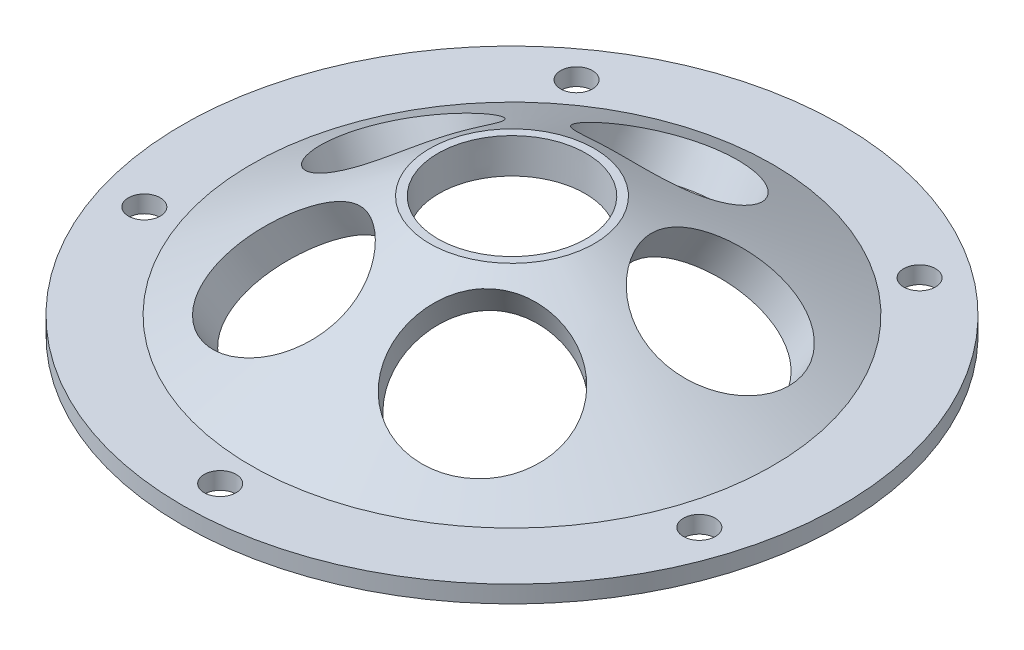
SolidWorks part; units mm, degrees
ref_plane "Front Plane" through (0, 0, 0) normal (0, 0, 1) x (1, 0, 0)
ref_plane "Top Plane" through (0, 0, 0) normal (0, 1, 0) x (1, 0, 0)
ref_plane "Right Plane" through (0, 0, 0) normal (1, 0, 0) x (0, 0, -1)
sketch "Sketch1" plane through (0, 0, 0) normal (0, 0, 1) x (1, 0, 0)
  line L0 (0, 0) -> (0, 62.5338) construction
  line L1 (-13.112, 0.0042) -> (-11.5245, -2.7454) construction
  line L2 (-7.62, 3.175) -> (0, 3.175)
  line L3 (0, 3.175) -> (0, 0)
  line L4 (0, 0) -> (-6.7693, 0)
  line L5 (-20.5296, -7.9446) -> (-6.7693, 0)
  line L6 (-20.5296, -7.9446) -> (-30.48, -7.9446)
  line L7 (-24.13, -6.3571) -> (-7.62, 3.175)
  line L8 (-24.13, -6.3571) -> (-30.48, -6.3571)
  line L9 (-30.48, -6.3571) -> (-30.48, -7.9446)
  dimension "D5" = 30.48
  dimension "D1" = 3.175
  dimension "D2" = 30
  dimension "D3" = 1.5875
  dimension "D4" = 3.175
  dimension "D6" = 7.62
  dimension "D7" = 30
  dimension "D8" = 6.35
revolve "Revolve1" add sketch "Sketch1" angle 360 about L0
hole_wizard "7/16 (0.4375) Diameter Hole1" positions "3DSketch3" profile "Sketch13" hole size "7/16" standard "ANSI Inch"
sketch3d "3DSketch3"
  line L0 (0, 0, 0) -> (-0.4067, -1.1972, -15.1875) construction
  point P0 (-0.4067, -1.1972, -15.1875)
  point P3 (0, 0, 0)
  dimension "D1" = 15.24
sketch "Sketch13" plane through (-0.4067, -1.1972, -15.1875) normal (0.6522, 0.3865, 0.6522) x (-0.758, 0.3172, 0.57)
  line L0 (0, 0) -> (0, 32.3745)
  line L1 (0, 32.3745) -> (5.5562, 32.3745)
  line L2 (5.5562, 32.3745) -> (5.5562, 0)
  line L5 (5.5562, 0) -> (0, 0)
  line L11 (0, -6.35) -> (0, 107.95) construction
  dimension "Thru Hole Dia." = 11.1125
  dimension "Thru Hole Depth" = 32.3745
hole_wizard "7/16 (0.4375) Diameter Hole2" positions "Sketch15" profile "Sketch14" hole size "7/16" standard "ANSI Inch"
sketch "Sketch15" plane through (0, 3.175, 0) normal (0, 1, 0) x (1, 0, 0)
  point P0 (0, 0)
sketch "Sketch14" plane through (0, 3.175, 0) normal (1, 0, 0) x (0, 0, 1)
  line L0 (0, 0) -> (0, 35.8505)
  line L1 (0, 35.8505) -> (5.5562, 32.512)
  line L2 (5.5562, 32.512) -> (5.5562, 0)
  line L5 (5.5562, 0) -> (0, 0)
  line L10 (0, 35.8505) -> (-5.5563, 32.512) construction
  line L11 (0, -6.35) -> (0, 107.95) construction
  dimension "Hole Dia." = 11.1125
  dimension "Hole Depth" = 32.512
  dimension "Drill Angle" = 118
pattern_circular "CirPattern2" count 5 over 360 about axis through (0, 3.175, 0) along (0, -1, 0) of "7/16 (0.4375) Diameter Hole1"
hole_wizard "1/4 NPT Tapped Hole4" positions "3DSketch4" profile "Sketch18" size "1/4" standard "ANSI Inch"
sketch3d "3DSketch4"
  line L0 (0, 0, 0) -> (0, 3.175, 0) construction
  point P0 (0, 3.175, 0)
sketch "Sketch18" plane through (0, 3.175, 0) normal (1, 0, 0) x (0, 0, 1)
  line L0 (0, 0) -> (0, 20.3603)
  line L1 (5.5626, 17.018) -> (0, 20.3603)
  line L2 (-5.5626, 17.018) -> (0, 20.3603) construction
  line L3 (5.5626, 17.018) -> (5.5626, 9.906)
  line L4 (5.5626, 9.906) -> (6.558, 9.906)
  line L5 (6.558, 9.906) -> (6.8546, 0)
  line L6 (-6.558, 9.906) -> (-6.8546, 0) construction
  line L7 (6.8546, 0) -> (0, 0)
  line L8 (0, -6.35) -> (0, 107.95) construction
  line L11 (-5.5626, 9.906) -> (-6.558, 9.906) construction
  dimension "Tap Drill Dia." = 11.1252
  dimension "Tap Drill Depth" = 17.018
  dimension "Thread Dia." = 13.7092
  dimension "Thread Angle" = 3.43
  dimension "Thread Depth" = 9.906
  dimension "Drill Angle" = 118
hole_wizard "1/4 NPT Tapped Hole5" positions "3DSketch5" profile "Sketch19" size "1/4" standard "ANSI Inch"
sketch3d "3DSketch5"
  line L0 (0, 0, 0) -> (-0.4041, -1.1972, -15.1875)
  point P0 (-0.4041, -1.1972, -15.1875)
  dimension "D1" = 15.24
sketch "Sketch19" plane through (-0.4041, -1.1972, -15.1875) normal (0.6522, 0.3864, 0.6522) x (-0.7579, 0.3173, 0.5699)
  line L0 (0, 0) -> (0, 20.3603)
  line L1 (5.5626, 17.018) -> (0, 20.3603)
  line L2 (-5.5626, 17.018) -> (0, 20.3603) construction
  line L3 (5.5626, 17.018) -> (5.5626, 9.906)
  line L4 (5.5626, 9.906) -> (6.558, 9.906)
  line L5 (6.558, 9.906) -> (6.8546, 0)
  line L6 (-6.558, 9.906) -> (-6.8546, 0) construction
  line L7 (6.8546, 0) -> (0, 0)
  line L8 (0, -6.35) -> (0, 107.95) construction
  line L11 (-5.5626, 9.906) -> (-6.558, 9.906) construction
  dimension "Tap Drill Dia." = 11.1252
  dimension "Tap Drill Depth" = 17.018
  dimension "Thread Dia." = 13.7092
  dimension "Thread Angle" = 3.43
  dimension "Thread Depth" = 9.906
  dimension "Drill Angle" = 118
pattern_circular "CirPattern3" count 5 over 360 about axis through (0, 3.175, 0) along (0, -1, 0) of "1/4 NPT Tapped Hole5"
hole_wizard "#4 Clearance Hole1" positions "Sketch21" profile "Sketch20" hole size "#4" standard "ANSI Inch"
sketch "Sketch21" plane through (0, -6.3571, 0) normal (0, 1, 0) x (1, 0, 0)
  line L0 (0, 0) -> (0, -26.9875) construction
  point P0 (0, -26.9875)
  dimension "D1" = 26.9875
sketch "Sketch20" plane through (0, -6.3571, 26.9875) normal (1, 0, 0) x (0, 0, 1)
  line L0 (0, 0) -> (0, 32.1272)
  line L1 (0, 32.1272) -> (1.4732, 31.242)
  line L2 (1.4732, 31.242) -> (1.4732, 0)
  line L5 (1.4732, 0) -> (0, 0)
  line L10 (0, 32.1272) -> (-1.4732, 31.242) construction
  line L11 (0, -6.35) -> (0, 107.95) construction
  dimension "Hole Dia." = 2.9464
  dimension "Hole Depth" = 31.242
  dimension "Drill Angle" = 118
pattern_circular "CirPattern4" count 5 over 360 about axis through (0, 0, 0) along (0, 1, 0) of "#4 Clearance Hole1"
